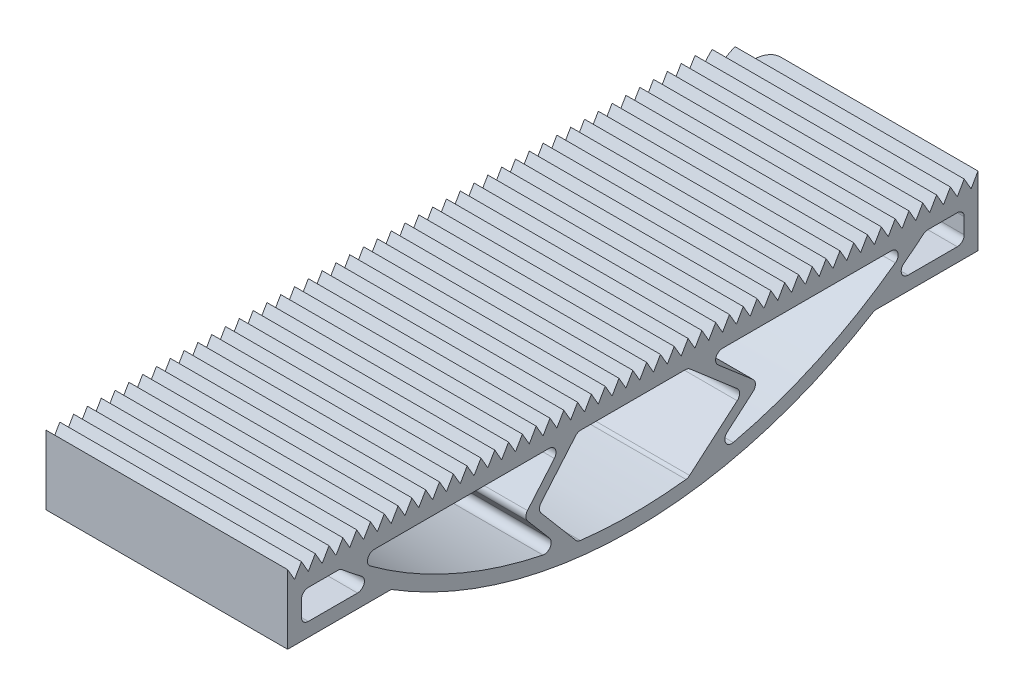
SolidWorks part; units mm, degrees
material "TPU_3C"
ref_plane "Front Plane" through (0, 0, 0) normal (0, 0, 1) x (1, 0, 0)
ref_plane "Top Plane" through (0, 0, 0) normal (0, 1, 0) x (1, 0, 0)
ref_plane "Right Plane" through (0, 0, 0) normal (1, 0, 0) x (0, 0, -1)
sketch "Sketch1" plane through (0, 0, 0) normal (0, 1, 0) x (1, 0, 0)
  line L1 (0, 0) -> (35, 0)
  line L2 (0, 0) -> (0, 100)
  line L3 (0, 100) -> (35, 100)
  line L4 (35, 0) -> (35, 100)
  dimension "D1" = 35
  dimension "D2" = 100
extrude "Boss-Extrude1" add sketch "Sketch1" along normal blind 10
sketch "Sketch3" plane through (0, 0, 0) normal (-1, 0, 0) x (0, 0, 1)
  line L0 (-100, 10) -> (-99, 8.2679)
  line L1 (-99, 8.2679) -> (-98, 10)
  line L2 (-100, 10) -> (0, 10) construction
  line L3 (-98, 10) -> (-100, 10)
  dimension "D1" = 2
  dimension "D2" = 2
  dimension "D3" = 2
extrude "Cut-Extrude1" cut sketch "Sketch3" against normal through all
pattern_linear "LPattern1" count 50 spacing 2 along (0, 0, 1) of "Cut-Extrude1"
sketch "Sketch4" plane through (35, 0, 0) normal (1, 0, 0) x (0, 0, -1)
  line L0 (0, 0) -> (100, 0) construction
  line L1 (15, 0) -> (85, 0)
  arc A0 (15, 0) -> (85, 0) centre (50, 56.25) ccw
  dimension "D1" = 15
  dimension "D2" = 15
  dimension "D3" = 10
extrude "Boss-Extrude2" add sketch "Sketch4" against normal blind 35
fillet "Fillet1" radius 6.5 1 edges at (0, 5, -100)
sketch "Sketch5" plane through (0, 0, 0) normal (-1, 0, 0) x (0, 0, 1)
  line L1 (-90.3715, 6.2679) -> (-9.6285, 6.2679)
  line L2 (-58, 6.2679) -> (-66, -0.616)
  line L3 (-66, -0.616) -> (-58, -7.5)
  line L6 (-60.7764, -7.0898) -> (-68.2997, -0.616)
  line L7 (-68.2997, -0.616) -> (-60.2997, 6.2679)
  line L10 (-42, 6.2679) -> (-36.1602, -0.616)
  line L11 (-36.1602, -0.616) -> (-42, -7.5)
  line L12 (-39.7605, -7.1788) -> (-34.1931, -0.616)
  line L13 (-34.1931, -0.616) -> (-40.033, 6.2679)
  line L14 (-100, 0) -> (-93.5, 0) construction
  line L15 (-98, 6.2679) -> (-92.3715, 6.2679)
  line L16 (-98, 6.2679) -> (-98, 2)
  line L17 (-98, 2) -> (-92.3715, 2)
  line L18 (-92.3715, 6.2679) -> (-92.3715, 2)
  line L19 (-2, 6.2679) -> (-7.6285, 6.2679)
  line L20 (-2, 6.2679) -> (-2, 2)
  line L21 (-2, 2) -> (-7.6285, 2)
  line L22 (-7.6285, 6.2679) -> (-7.6285, 2)
  line L23 (-100, 0) -> (-100, 10) construction
  line L24 (-15, 0) -> (0, 0) construction
  line L25 (0, 10) -> (0, 0) construction
  line L26 (-92.3715, 2) -> (-86.749, 2)
  line L27 (-13.251, 2) -> (-7.6285, 2)
  arc A1 (-92.3715, 6.2679) -> (-86.749, 2) centre (-50, 56.25) ccw
  arc A2 (-90.3715, 6.2679) -> (-9.6285, 6.2679) centre (-50, 56.25) ccw
  arc A3 (-85, 0) -> (-15, 0) centre (-50, 56.25) ccw construction
  arc A4 (-7.6285, 6.2679) -> (-13.251, 2) centre (-50, 56.25) cw
  point P17 (-50, 6.2679)
  dimension "D1" = 2
  dimension "D2" = 2
  dimension "D3" = 1.5
  dimension "D4" = 1.5
  dimension "D5" = 1.5
  dimension "D6" = 1.5
  dimension "D7" = 8
  dimension "D8" = 8
  dimension "D9" = 8
  dimension "D10" = 2
  dimension "D11" = 2
  dimension "D12" = 2
  dimension "D13" = 2
  dimension "D14" = 2
  dimension "D15" = 2
extrude "Cut-Extrude2" cut sketch "Sketch5" against normal through all contours L18 L15 L16 L17 | A1 L18 L26 | L1 A2 L6 L7 | L3 A2 L11 L10 L1 L2 | L12 A2 L1 L13 | L19 L22 L21 L20 | L22 A4 L27
fillet "Fillet2" radius 1 22 edges at (17.5, 6.2679, -7.6285) (17.5, 2, -13.251) (17.5, 2, -2) (17.5, 6.2679, -2) (17.5, 6.2679, -90.3715) (17.5, 6.2679, -9.6285) (17.5, -7.1788, -39.7605) (17.5, -0.616, -34.1931) (17.5, 6.2679, -40.033) (17.5, -7.5, -42) (17.5, -0.616, -36.1602) (17.5, 6.2679, -42) (17.5, 6.2679, -58) (17.5, -7.5, -58) (17.5, -0.616, -66) (17.5, -7.0898, -60.7764) (17.5, 6.2679, -60.2997) (17.5, -0.616, -68.2997) (18.4048, 2, -98) (17.5, 2, -86.749) (17.5, 6.2679, -92.3715) (18.4048, 6.2679, -98)
